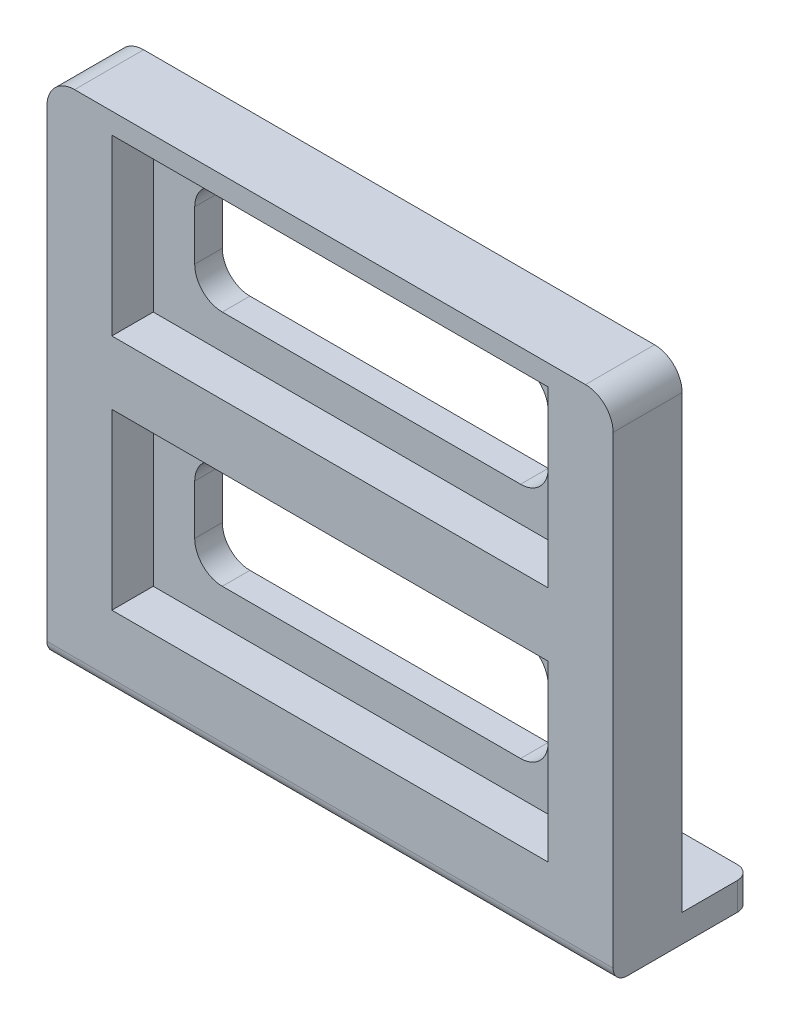
SolidWorks part; units mm, degrees
ref_plane "Front Plane" through (0, 0, 0) normal (0, 0, 1) x (1, 0, 0)
ref_plane "Top Plane" through (0, 0, 0) normal (0, 1, 0) x (1, 0, 0)
ref_plane "Right Plane" through (0, 0, 0) normal (1, 0, 0) x (0, 0, -1)
sketch "Sketch1" plane through (0, 0, 0) normal (0, 0, 1) x (1, 0, 0)
  line L1 (-21.5, -18) -> (20.5, -18)
  line L2 (-21.5, -18) -> (-21.5, 22.2)
  line L3 (-21.5, 22.2) -> (20.5, 22.2)
  line L4 (20.5, -18) -> (20.5, 22.2)
  line L5 (-21.5, -18) -> (20.5, 22.2) construction
  line L6 (-21.5, 22.2) -> (20.5, -18) construction
  point P0 (-0.5, 2.1)
  dimension "D1" = 42
  dimension "D2" = 40.2
extrude "Boss-Extrude1" add sketch "Sketch1" along normal blind 5
sketch "Sketch2" plane through (0, 0, 5) normal (0, 0, 1) x (1, 0, 0)
  line L0 (20.5, 22.2) -> (-21.5, 22.2) construction
  line L1 (-16.8, 17) -> (14.8, 17)
  line L2 (-16.8, 17) -> (-16.8, 4.4)
  line L3 (-16.8, 4.4) -> (14.8, 4.4)
  line L4 (14.8, 17) -> (14.8, 4.4)
  line L5 (-16.8, -0.2) -> (14.8, -0.2)
  line L6 (-16.8, -0.2) -> (-16.8, -12.8)
  line L7 (-16.8, -12.8) -> (14.8, -12.8)
  line L8 (14.8, -0.2) -> (14.8, -12.8)
  line L9 (-21.5, -18) -> (20.5, -18) construction
  line L10 (-21.5, 22.2) -> (-21.5, -18) construction
  dimension "D1" = 31.6
  dimension "D2" = 12.6
  dimension "D3" = 12.6
  dimension "D4" = 31.6
  dimension "D5" = 5.2
  dimension "D6" = 5.2
  dimension "D7" = 4.7
  dimension "D8" = 4.7
extrude "Cut-Extrude1" cut sketch "Sketch2" against normal blind 3
sketch "Sketch3" plane through (0, 0, 2) normal (0, 0, 1) x (1, 0, 0)
  line L0 (14.8, 17) -> (-16.8, 17) construction
  line L1 (-13.8, 14.5) -> (11.8, 14.5)
  line L2 (-13.8, 14.5) -> (-13.8, 6.9)
  line L3 (-13.8, 6.9) -> (11.8, 6.9)
  line L4 (11.8, 14.5) -> (11.8, 6.9)
  line L5 (-13.8, -2.7) -> (11.8, -2.7)
  line L6 (-13.8, -2.7) -> (-13.8, -10.3)
  line L7 (-13.8, -10.3) -> (11.8, -10.3)
  line L8 (11.8, -2.7) -> (11.8, -10.3)
  line L9 (-16.8, 17) -> (-16.8, 4.4) construction
  line L10 (14.8, 4.4) -> (14.8, 17) construction
  line L11 (-16.8, 4.4) -> (14.8, 4.4) construction
  line L12 (14.8, -0.2) -> (-16.8, -0.2) construction
  line L13 (-16.8, -12.8) -> (14.8, -12.8) construction
  line L14 (14.8, -12.8) -> (14.8, -0.2) construction
  line L15 (-16.8, -0.2) -> (-16.8, -12.8) construction
  dimension "D1" = 2.5
  dimension "D2" = 3
  dimension "D3" = 3
  dimension "D4" = 2.5
  dimension "D5" = 2.5
  dimension "D6" = 2.5
  dimension "D7" = 3
  dimension "D8" = 3
extrude "Cut-Extrude2" cut sketch "Sketch3" against normal blind 3
sketch "Sketch4" plane through (0, 0, 0) normal (0, 0, -1) x (-1, 0, 0)
  line L0 (21.5, 22.2) -> (21.5, -18) construction
  line L1 (-20.5, 22.2) -> (21.5, 22.2)
  line L2 (-20.5, 22.2) -> (-20.5, 16.3079)
  line L3 (-19.5, 18.5) -> (21.5, 18.5)
  line L4 (21.5, 22.2) -> (21.5, 16.3079)
  line L5 (-11.8, 14.5) -> (-11.8, 6.9) construction
  line L6 (-20.5, -18) -> (21.5, -18)
  line L7 (-20.5, -18) -> (-20.5, -16.8347)
  line L8 (-19.5, -16.1) -> (21.5, -16.1)
  line L9 (21.5, -18) -> (21.5, -16.8347)
  line L10 (21.5, -18) -> (16.3138, -18)
  line L11 (21.5, -18) -> (21.5, 22.2)
  line L12 (21.5, 22.2) -> (16.3138, 22.2)
  line L13 (21.5, -16.1) -> (21.5, 18.5)
  line L14 (-20.5, 22.2) -> (-15.2886, 22.2)
  line L15 (-20.5, 22.2) -> (-20.5, -18)
  line L16 (-20.5, -18) -> (-15.2886, -18)
  line L17 (-19.5, 18.5) -> (-19.5, -16.1)
  line L18 (13.8, 14.5) -> (-11.8, 14.5) construction
  line L19 (13.8, 6.9) -> (13.8, 14.5) construction
  line L20 (13.8, -10.3) -> (-11.8, -10.3) construction
  line M9 (-20.5, 22.2) -> (-20.5, -18)
  line M10 (-20.5, -18) -> (21.5, -18)
  line M11 (21.5, -18) -> (21.5, 22.2)
  line M12 (21.5, 22.2) -> (-20.5, 22.2)
  dimension "D1" = 7.7
  dimension "D2" = 4
  dimension "D3" = 7.7
  dimension "D4" = 5.8
extrude "Cut-Extrude3" cut sketch "Sketch4" against normal blind 5 contours L1 L6 L17 L3 L13 L8 M12 M9 M10 M11
fillet "Fillet1" radius 2 10 edges at (-13.8, 6.9, 1) (-13.8, 14.5, 1) (11.8, 6.9, 1) (11.8, 14.5, 1) (-13.8, -10.3, 1) (-13.8, -2.7, 1) (11.8, -2.7, 1) (11.8, -10.3, 1) (19.5, 18.5, 2.5) (-21.5, 18.5, 2.5)
sketch "Sketch7" [suppressed] plane through (0, -20.3, 0) normal (0, -1, 0) x (1, 0, 0)
  line L0 (-7.8, 5) -> (-10.8, 5) construction
  line L1 (-10.8, -5) -> (-7.8, -5) construction
  line L2 (10.8, 5) -> (7.8, 5) construction
  line L3 (7.8, -5) -> (10.8, -5) construction
  line L4 (10.8, -5) -> (10.8, 5) construction
  line L5 (-10.8, 5) -> (-10.8, -5) construction
  circle A0 centre (9.3, 3.5) radius 1
  circle A1 centre (9.3, -2.5) radius 1
  circle A2 centre (-9.3, 3.5) radius 1
  circle A3 centre (-9.3, -2.5) radius 1
  dimension "D1" = 1.5
  dimension "D9" = 2
  dimension "D10" = 2
  dimension "D11" = 2
  dimension "D12" = 2
  dimension "D2" = 2.5
  dimension "D3" = 1.5
  dimension "D4" = 2.5
  dimension "D5" = 1.5
  dimension "D6" = 1.5
  dimension "D7" = 1.5
  dimension "D8" = 1.5
extrude "Cut-Extrude4" [suppressed] cut sketch "Sketch7" against normal blind 5
sketch "Sketch9" plane through (0, 0, 5) normal (0, 0, 1) x (1, 0, 0)
  line L1 (-21.5, -16.1) -> (19.5, -16.1)
  line L2 (-21.5, -16.1) -> (-21.5, -18.1)
  line L3 (-21.5, -18.1) -> (19.5, -18.1)
  line L4 (19.5, -16.1) -> (19.5, -18.1)
  point P5 (0, 0)
  dimension "D1" = 2
extrude "Boss-Extrude3" add sketch "Sketch9" against normal blind 10
fillet "Fillet2" radius 1 1 edges at (-1, -18.1, 5)
hole_wizard "Tap Drill for M3 Tap1" positions "Sketch10" profile "Sketch11" hole size "M3" standard "ISO"
sketch "Sketch10" plane through (0, -16.1, 0) normal (0, 1, 0) x (1, 0, 0)
  line L0 (-21.5, 5) -> (-21.5, 0) construction
  point P0 (14, 2.8774)
  point P2 (4, 2.8774)
  point P4 (-6, 2.8774)
  point P6 (-16, 2.8774)
  point P11 (-21.5, 2.5)
  point P12 (0, 0)
  dimension "D1" = 10
  dimension "D2" = 10
  dimension "D3" = 10
  dimension "D4" = 5.5
sketch "Sketch11" plane through (14, -16.1, -2.8774) normal (1, 0, 0) x (0, 0, 1)
  line L0 (0, 0) -> (0, 2.7511)
  line L1 (0, 2.7511) -> (1.25, 2)
  line L2 (1.25, 2) -> (1.25, 0)
  line L5 (1.25, 0) -> (0, 0)
  line L10 (0, 2.7511) -> (-1.25, 2) construction
  line L11 (0, -6.35) -> (0, 107.95) construction
  dimension "Hole Dia." = 2.5
  dimension "Hole Depth" = 2
  dimension "Drill Angle" = 118
fillet "Fillet3" radius 1 2 edges at (19.5, -17.1, -5) (-21.5, -17.1, -5)
